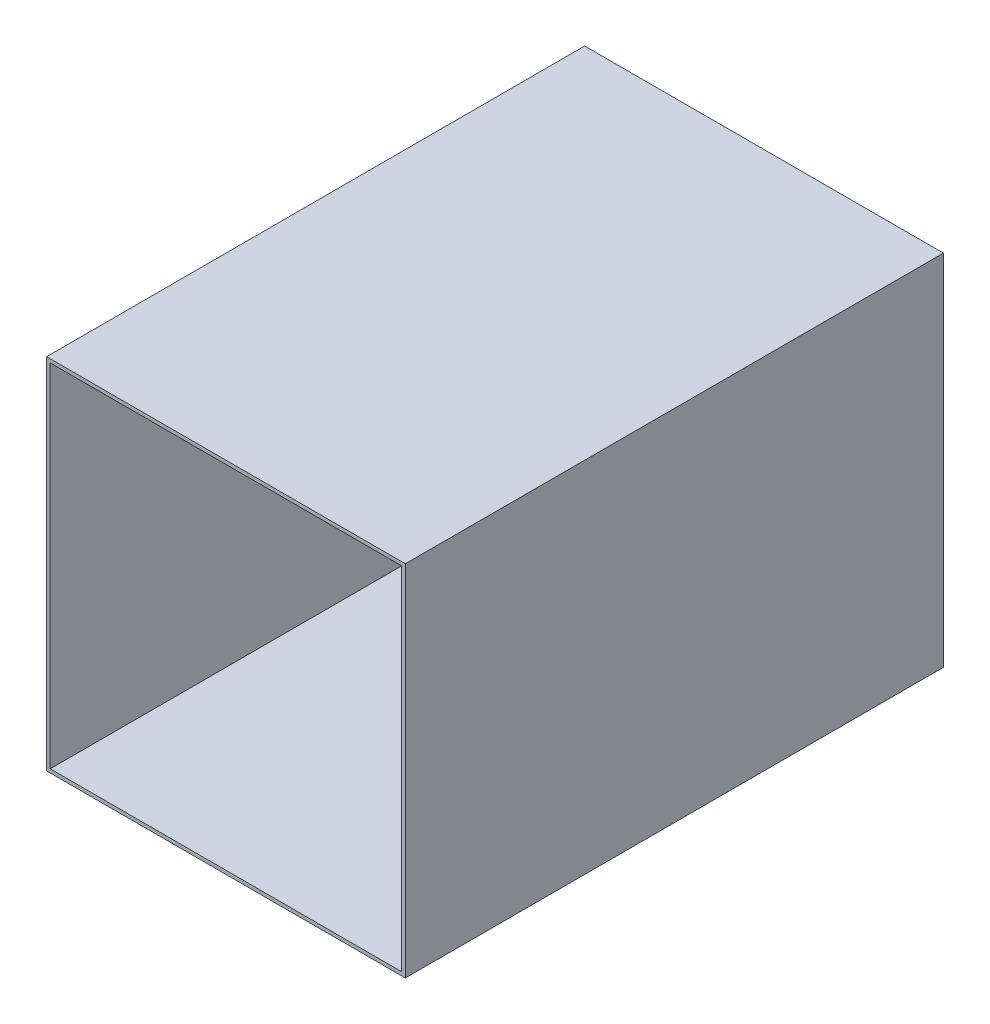
SolidWorks part; units mm, degrees
ref_plane "前视基准面" through (0, 0, 0) normal (0, 0, 1) x (1, 0, 0)
ref_plane "上视基准面" through (0, 0, 0) normal (0, 1, 0) x (1, 0, 0)
ref_plane "右视基准面" through (0, 0, 0) normal (1, 0, 0) x (0, 0, -1)
other "Configuration Table"
sketch "草图1" plane through (0, 0, 0) normal (0, 0, 1) x (1, 0, 0)
  line L1 (-100, -100) -> (100, -100)
  line L2 (-100, -100) -> (-100, 100)
  line L3 (-100, 100) -> (100, 100)
  line L4 (100, -100) -> (100, 100)
  line L5 (-100, -100) -> (100, 100) construction
  line L6 (-100, 100) -> (100, -100) construction
  line L7 (-98, 98) -> (98, 98)
  line L8 (-98, 98) -> (-98, -98)
  line L9 (-98, -98) -> (98, -98)
  line L10 (98, 98) -> (98, -98)
  line L11 (-98, 98) -> (98, -98) construction
  line L12 (-98, -98) -> (98, 98) construction
  point P0 (0, 0)
  point P5 (0, 0)
  dimension "D1" = 200
  dimension "D2" = 200
  dimension "D3" = 2
extrude "凸台-拉伸1" add sketch "草图1" along normal mid plane 300
